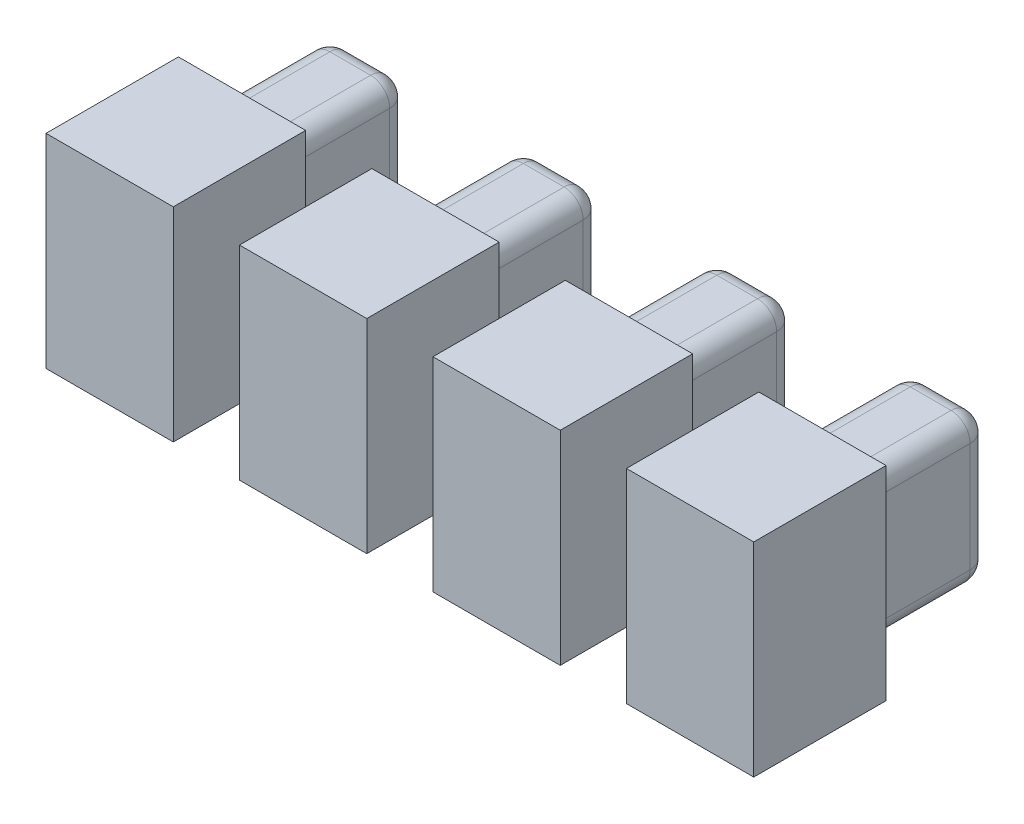
SolidWorks part; units mm, degrees
ref_plane "前视基准面" through (0, 0, 0) normal (0, 0, 1) x (1, 0, 0)
ref_plane "上视基准面" through (0, 0, 0) normal (0, 1, 0) x (1, 0, 0)
ref_plane "右视基准面" through (0, 0, 0) normal (1, 0, 0) x (0, 0, -1)
sketch "草图1" plane through (0, 0, 0) normal (0, 0, 1) x (1, 0, 0)
  line L0 (5, 4.6003) -> (0, 4.6003)
  line L13 (-2.6, 4.6003) -> (-7.6, 4.6003)
  line L14 (-2.6, 4.6003) -> (-2.6, -3.3997)
  line L19 (-2.6, -3.3997) -> (-7.6, -3.3997)
  line L20 (-7.6, 4.6003) -> (-7.6, -3.3997)
  line L21 (-5.1, -3.3997) -> (-5.1, 4.6003) construction
  line L22 (-2.6, 0.6003) -> (-7.6, 0.6003) construction
  line L23 (5, 4.6003) -> (5, -3.3997)
  line L24 (5, -3.3997) -> (0, -3.3997)
  line L25 (0, 4.6003) -> (0, -3.3997)
  line L26 (2.5, -3.3997) -> (2.5, 4.6003) construction
  line L27 (5, 0.6003) -> (0, 0.6003) construction
  line L28 (12.6, 4.6003) -> (7.6, 4.6003)
  line L29 (12.6, 4.6003) -> (12.6, -3.3997)
  line L30 (12.6, -3.3997) -> (7.6, -3.3997)
  line L31 (7.6, 4.6003) -> (7.6, -3.3997)
  line L32 (10.1, -3.3997) -> (10.1, 4.6003) construction
  line L33 (12.6, 0.6003) -> (7.6, 0.6003) construction
  line L34 (20.2, 4.6003) -> (15.2, 4.6003)
  line L35 (20.2, 4.6003) -> (20.2, -3.3997)
  line L36 (20.2, -3.3997) -> (15.2, -3.3997)
  line L37 (15.2, 4.6003) -> (15.2, -3.3997)
  line L38 (17.7, -3.3997) -> (17.7, 4.6003) construction
  line L39 (20.2, 0.6003) -> (15.2, 0.6003) construction
  point P0 (-5.1, 0.6003)
  point P6 (2.5, 0.6003)
  point P18 (10.1, 0.6003)
  point P27 (17.7, 0.6003)
  dimension "D1" = 2.6
  dimension "D2" = 5
  dimension "D3" = 8
  dimension "D4" = 4
extrude "凸台-拉伸1" add sketch "草图1" along normal blind 5.2
sketch "草图2" plane through (0, 0, 0) normal (0, 0, -1) x (-1, 0, 0)
  line L8 (-16.15, 3.5003) -> (-16.15, -2.2997)
  line L9 (-16.15, -2.2997) -> (-19.25, -2.2997)
  line L10 (-19.25, -2.2997) -> (-19.25, 3.5003)
  line L11 (-19.25, 3.5003) -> (-16.15, 3.5003)
  line L12 (-8.55, 3.5003) -> (-8.55, -2.2997)
  line L13 (-8.55, -2.2997) -> (-11.65, -2.2997)
  line L14 (-11.65, -2.2997) -> (-11.65, 3.5003)
  line L15 (-11.65, 3.5003) -> (-8.55, 3.5003)
  line L16 (-0.95, 3.5003) -> (-0.95, -2.2997)
  line L17 (-0.95, -2.2997) -> (-4.05, -2.2997)
  line L18 (-4.05, -2.2997) -> (-4.05, 3.5003)
  line L19 (-4.05, 3.5003) -> (-0.95, 3.5003)
  line L20 (6.65, 3.5003) -> (6.65, -2.2997)
  line L21 (6.65, -2.2997) -> (3.55, -2.2997)
  line L22 (3.55, -2.2997) -> (3.55, 3.5003)
  line L23 (3.55, 3.5003) -> (6.65, 3.5003)
  line L24 (-20.2, -3.3997) -> (-20.2, 4.6003) construction
  line L25 (-15.2, 4.6003) -> (-15.2, -3.3997) construction
  line L26 (-20.2, 4.6003) -> (-15.2, 4.6003) construction
  dimension "D2" = 0.95
  dimension "D3" = 5.8
  dimension "D4" = 3.1
  dimension "D5" = 0.95
  dimension "D6" = 1.1
  dimension "D1" = 4
extrude "凸台-拉伸2" add sketch "草图2" along normal blind 5
sketch "草图3" plane through (0, 0, 0) normal (0, 1, 0) x (1, 0, 0)
  line L0 (0, -5.2) -> (0, 0) construction
  line L65 (-2.6, 0) -> (0, 0)
  line L66 (-2.6, 0) -> (-2.6, -0.6)
  line L67 (-2.6, -0.6) -> (0, -0.6)
  line L68 (0, 0) -> (0, -0.6)
  line L69 (7.6, -5.2) -> (7.6, 0) construction
  line L70 (5, 0) -> (7.6, 0)
  line L71 (5, 0) -> (5, -0.6)
  line L72 (5, -0.6) -> (7.6, -0.6)
  line L73 (7.6, 0) -> (7.6, -0.6)
  line L74 (15.2, -5.2) -> (15.2, 0) construction
  line L75 (12.6, 0) -> (15.2, 0)
  line L76 (12.6, 0) -> (12.6, -0.6)
  line L77 (12.6, -0.6) -> (15.2, -0.6)
  line L78 (15.2, 0) -> (15.2, -0.6)
  dimension "D1" = 3
extrude "凸台-拉伸3" add sketch "草图3" along normal blind 2 and the other way blind 1
fillet "圆角1" radius 0.75 32 edges at (16.15, 0.6003, -5) (17.7, -2.2997, -5) (19.25, 0.6003, -5) (17.7, 3.5003, -5) (8.55, 0.6003, -5) (10.1, -2.2997, -5) (11.65, 0.6003, -5) (10.1, 3.5003, -5) (0.95, 0.6003, -5) (2.5, -2.2997, -5) (4.05, 0.6003, -5) (2.5, 3.5003, -5) (-6.65, 0.6003, -5) (-5.1, -2.2997, -5) (-3.55, 0.6003, -5) (-5.1, 3.5003, -5) (16.15, 3.5003, -2.5) (11.65, 3.5003, -2.5) (8.55, -2.2997, -2.5) (8.55, 3.5003, -2.5) (4.05, 3.5003, -2.5) (4.05, -2.2997, -2.5) (0.95, -2.2997, -2.5) (0.95, 3.5003, -2.5) (-3.55, 3.5003, -2.5) (-3.55, -2.2997, -2.5) (-6.65, -2.2997, -2.5) (-6.65, 3.5003, -2.5) (11.65, -2.2997, -2.5) (16.15, -2.2997, -2.5) (19.25, -2.2997, -2.5) (19.25, 3.5003, -2.5)
